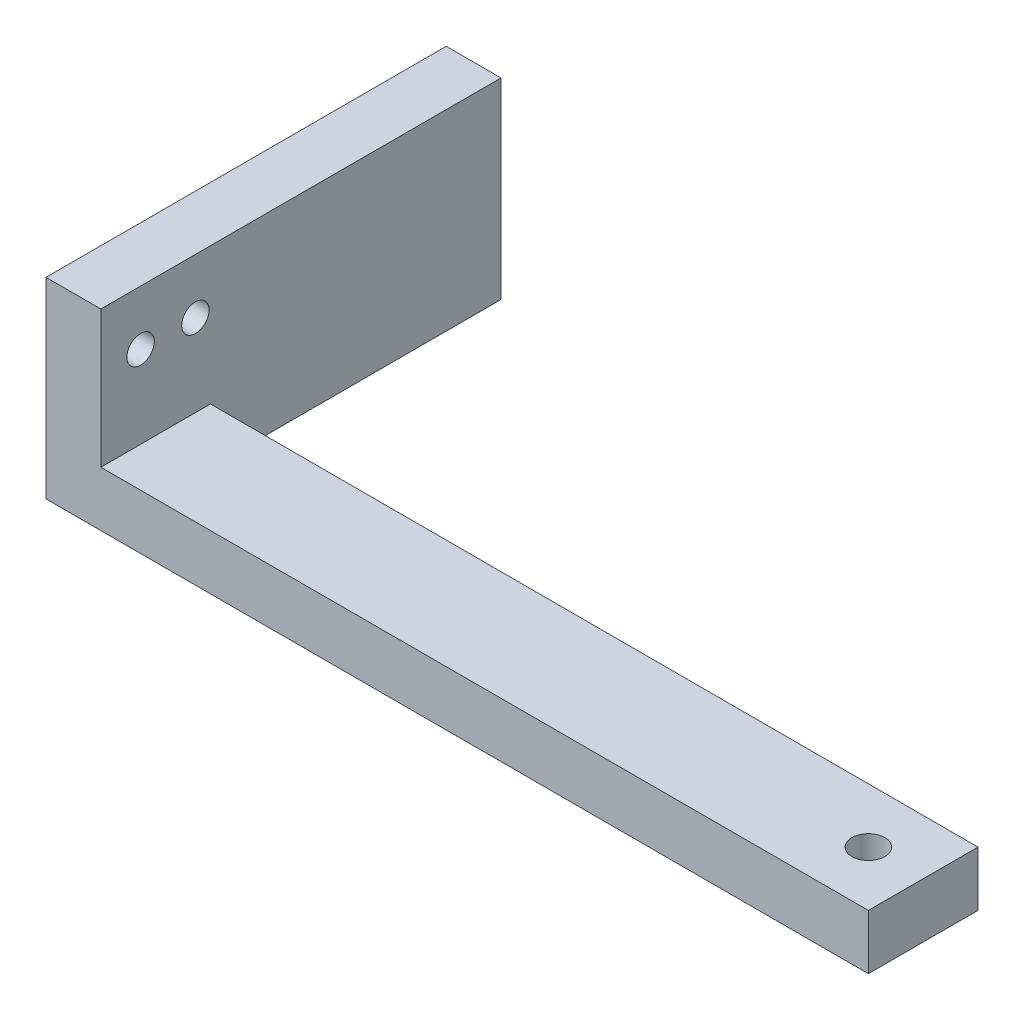
SolidWorks part; units mm, degrees
material "1060 Alloy"
ref_plane "Front Plane" through (0, 0, 0) normal (0, 0, 1) x (1, 0, 0)
ref_plane "Top Plane" through (0, 0, 0) normal (0, 1, 0) x (1, 0, 0)
ref_plane "Right Plane" through (0, 0, 0) normal (1, 0, 0) x (0, 0, -1)
sketch "Sketch1" plane through (0, 0, 0) normal (0, 1, 0) x (1, 0, 0)
  line L1 (-2547.7707, 451.1677) -> (-2397.7707, 451.1677)
  line L2 (-2547.7707, 451.1677) -> (-2547.7707, 431.1677)
  line L3 (-2547.7707, 431.1677) -> (-2397.7707, 431.1677)
  line L4 (-2397.7707, 451.1677) -> (-2397.7707, 431.1677)
  dimension "D1" = 150
  dimension "D2" = 20
extrude "Boss-Extrude1" add sketch "Sketch1" along normal blind 10
sketch "Sketch2" plane through (0, 10, 0) normal (0, 1, 0) x (1, 0, 0)
  line L0 (-2397.7707, 431.1677) -> (-2397.7707, 451.1677) construction
  circle A0 centre (-2407.7707, 441.1677) radius 3
  point P4 (-2397.7707, 441.1677)
  dimension "D1" = 6
  dimension "D2" = 10
extrude "Cut-Extrude1" cut sketch "Sketch2" against normal blind 10
sketch "Sketch3" plane through (-2547.7707, 0, 0) normal (-1, 0, 0) x (0, 0, 1)
  line L1 (-451.1677, 10) -> (-431.1677, 10) construction
  line L2 (-454.1677, 35) -> (-431.1677, 35)
  line L3 (-454.1677, 35) -> (-454.1677, 10)
  line L4 (-454.1677, 10) -> (-431.1677, 10)
  line L5 (-431.1677, 35) -> (-431.1677, 10)
  line L6 (-454.1677, 35) -> (-431.1677, 10) construction
  line L7 (-454.1677, 10) -> (-431.1677, 35) construction
  line L8 (-431.1677, 10) -> (-431.1677, 0) construction
  point P2 (-442.6677, 22.5)
  dimension "D1" = 23
  dimension "D2" = 25
extrude "Boss-Extrude2" add sketch "Sketch3" against normal blind 10
sketch "Sketch4" plane through (-2547.7707, 0, 0) normal (-1, 0, 0) x (0, 0, 1)
  line L0 (-431.1677, 35) -> (-454.1677, 35) construction
  line L1 (-454.1677, 35) -> (-454.1677, 10) construction
  circle A0 centre (-448.4177, 25) radius 2.5
  circle A2 centre (-438.4177, 25) radius 2.5
  dimension "D1" = 5
  dimension "D2" = 5
  dimension "D3" = 10
  dimension "D4" = 10
  dimension "D5" = 5.75
extrude "Cut-Extrude2" cut sketch "Sketch4" against normal through all
sketch "Sketch5" plane through (0, 0, -431.1677) normal (0, 0, 1) x (1, 0, 0)
  line L0 (-2537.7707, 10) -> (-2537.7707, 35) construction
  line L1 (-2547.7707, 35) -> (-2537.7707, 35)
  line L2 (-2547.7707, 35) -> (-2547.7707, 0)
  line L3 (-2547.7707, 0) -> (-2537.7707, 0)
  line L4 (-2537.7707, 35) -> (-2537.7707, 0)
  line L5 (-2547.7707, 35) -> (-2537.7707, 0) construction
  line L6 (-2547.7707, 0) -> (-2537.7707, 35) construction
  line L7 (-2547.7707, 35) -> (-2547.7707, 0) construction
  line L8 (-2537.7707, 35) -> (-2547.7707, 35) construction
  line L9 (-2547.7707, 0) -> (-2397.7707, 0) construction
  point P0 (-2542.7707, 17.5)
extrude "Boss-Extrude4" add sketch "Sketch5" against normal blind 53 from offset 20 offset against normal yes
